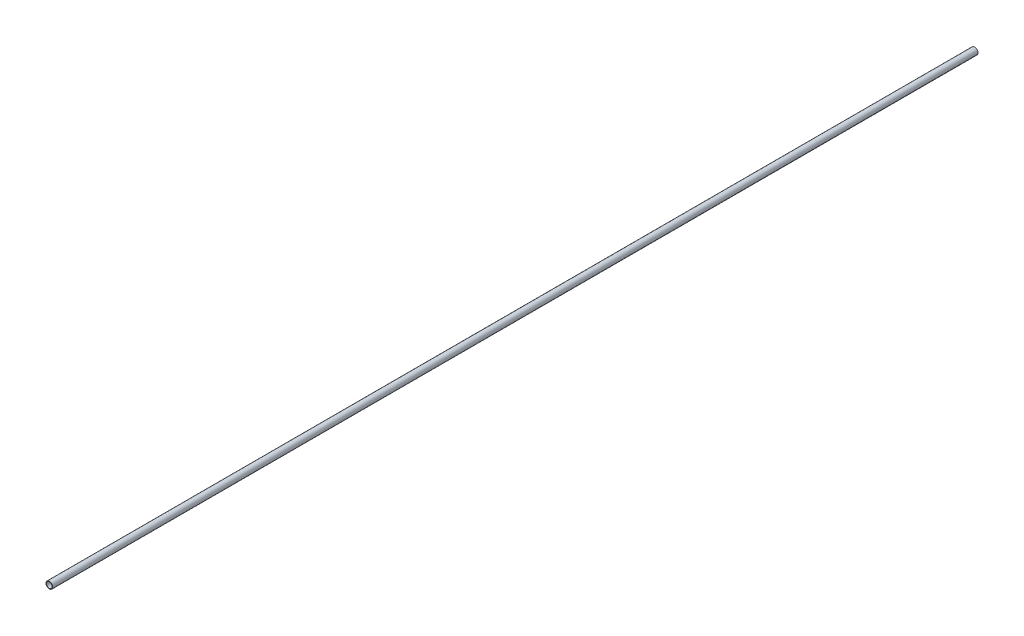
SolidWorks part; units mm, degrees
ref_plane "Front Plane" through (0, 0, 0) normal (0, 0, 1) x (1, 0, 0)
ref_plane "Top Plane" through (0, 0, 0) normal (0, 1, 0) x (1, 0, 0)
ref_plane "Right Plane" through (0, 0, 0) normal (1, 0, 0) x (0, 0, -1)
sketch "Sketch1" plane through (0, 0, 0) normal (0, 0, 1) x (1, 0, 0)
  circle A0 centre (0, 0) radius 31.75
  circle A1 centre (0, 0) radius 38.1
  dimension "D1" = 76.2
  dimension "D2" = 63.5
extrude "Boss-Extrude1" add sketch "Sketch1" along normal blind 10491.9868
equation "\"Do\"= 3in"
equation "\"t\"= .25in"
equation "\"Di\"= \"Do\" - 2 * \"t\""
equation "\"P\"= 400"
equation "\"E\" = 8500000"
equation "\"AD\"= .009in"
equation "\"A\"= ( pi / 4 ) * ( \"Do\" ^ 2 - \"Di\" ^ 2 )"
equation "\"L\"= \"AD\" * \"E\" * \"A\" * ( 1 / \"P\" )"
equation "\"W\"= .0975 * \"A\" * \"L\""
equation "\"D1@Sketch1\"=\"Do\""
equation "\"D2@Sketch1\"=\"Di\""
equation "\"D1@Boss-Extrude1\"=\"L\""
